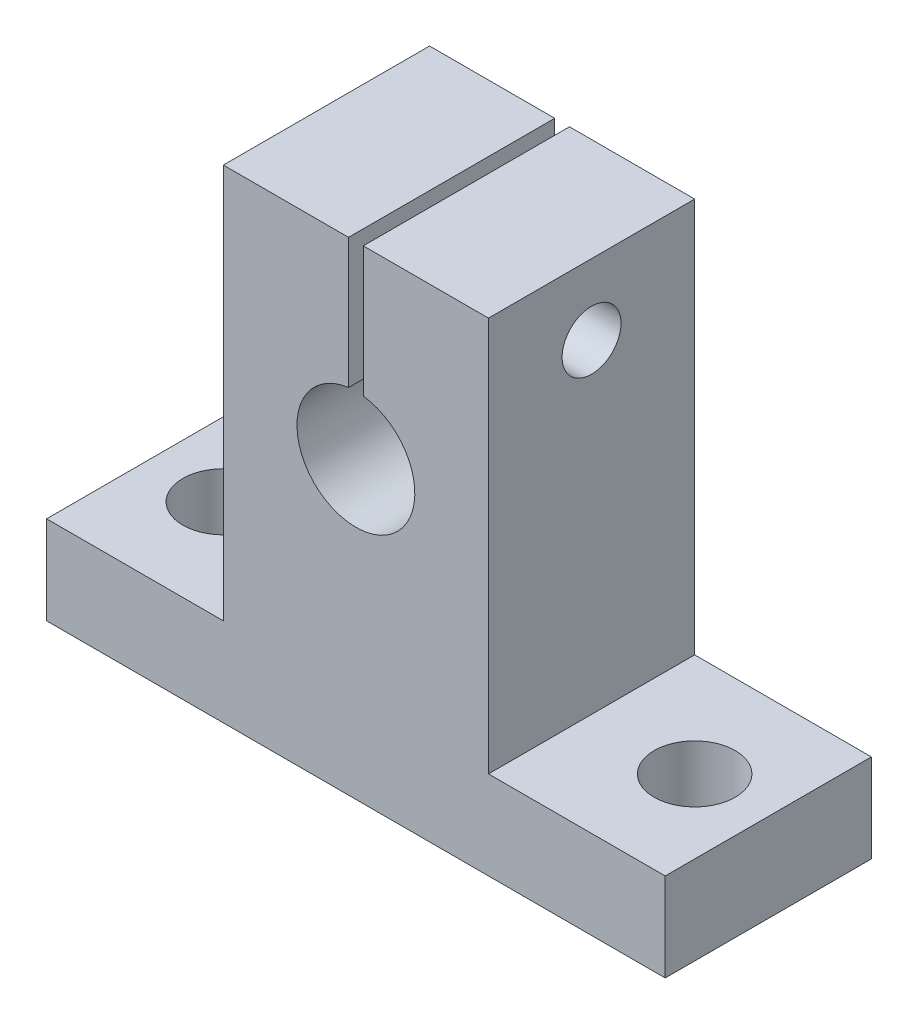
SolidWorks part; units mm, degrees
ref_plane "Front Plane" through (0, 0, 0) normal (0, 0, 1) x (1, 0, 0)
ref_plane "Top Plane" through (0, 0, 0) normal (0, 1, 0) x (1, 0, 0)
ref_plane "Right Plane" through (0, 0, 0) normal (1, 0, 0) x (0, 0, -1)
sketch "Sketch1" plane through (0, 0, 0) normal (0, 0, 1) x (1, 0, 0)
  line L0 (0.5, 32.8) -> (9, 32.8)
  line L2 (-9, 6) -> (-9, 32.8)
  line L3 (-9, 32.8) -> (-0.5, 32.8)
  line L4 (9, 6) -> (9, 32.8)
  line L5 (-0.5, 32.8) -> (-0.5, 23.9686)
  line L7 (-21, 0) -> (21, 0)
  line L8 (-21, 0) -> (-21, 6)
  line L9 (-21, 6) -> (-9, 6)
  line L10 (21, 0) -> (21, 6)
  line L11 (9, 6) -> (21, 6)
  line L12 (0.5, 32.8) -> (0.5, 23.9686)
  arc A0 (-0.5, 23.9686) -> (0.5, 23.9686) centre (0, 20) ccw
  point P0 (0, 0)
  dimension "D9" = 8
  dimension "D1" = 18
  dimension "D2" = 9
  dimension "D3" = 6
  dimension "D4" = 42
  dimension "D5" = 21
  dimension "D6" = 32.8
  dimension "D7" = 0
  dimension "D8" = 20
  dimension "D10" = 0
  dimension "D11" = 0.5
  dimension "D12" = 8.8314
extrude "Boss-Extrude1" add sketch "Sketch1" along normal mid plane 14
sketch "Sketch2" plane through (0, 6, 0) normal (0, 1, 0) x (1, 0, 0)
  circle A0 centre (-16, 0) radius 2.75
  circle A1 centre (16, 0) radius 2.75
  dimension "D3" = 5.5
  dimension "D1" = 16
  dimension "D2" = 32
extrude "Cut-Extrude1" cut sketch "Sketch2" against normal blind 14
sketch "Sketch3" plane through (9, 0, 0) normal (1, 0, 0) x (0, 0, -1)
  circle A0 centre (0, 28) radius 2
  dimension "D1" = 4
  dimension "D2" = 28
extrude "Cut-Extrude2" cut sketch "Sketch3" against normal blind 19
